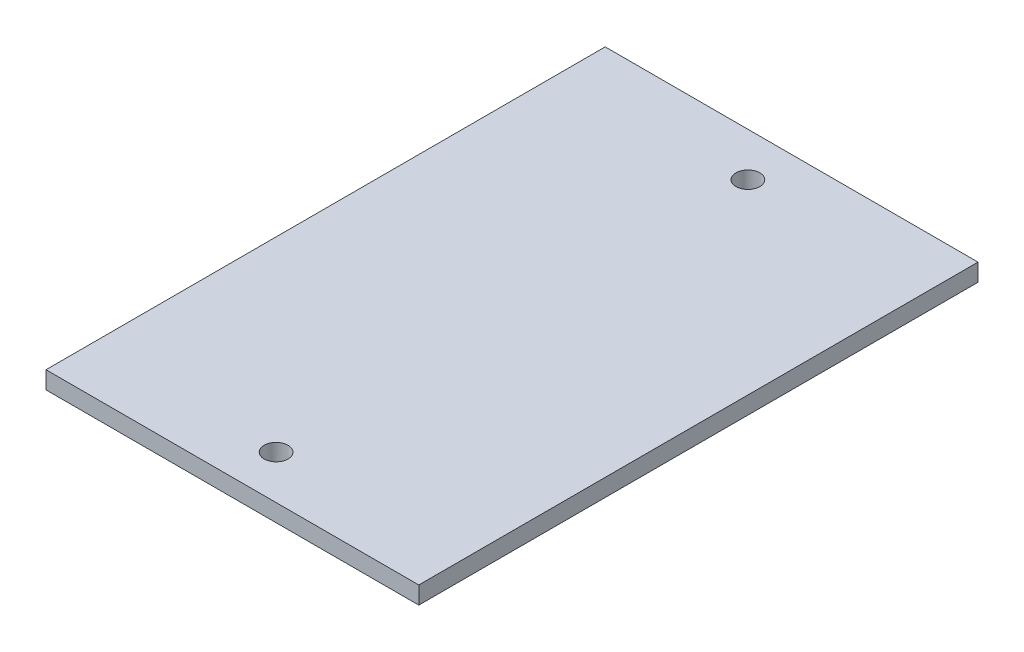
SolidWorks part; units mm, degrees
material "ABS"
ref_plane "Front Plane" through (0, 0, 0) normal (0, 0, 1) x (1, 0, 0)
ref_plane "Top Plane" through (0, 0, 0) normal (0, 1, 0) x (1, 0, 0)
ref_plane "Right Plane" through (0, 0, 0) normal (1, 0, 0) x (0, 0, -1)
sketch "Sketch1" plane through (0, 0, 0) normal (0, 1, 0) x (1, 0, 0)
  line L1 (0, 0) -> (64, 0)
  line L2 (0, 0) -> (0, -96)
  line L3 (0, -96) -> (64, -96)
  line L4 (64, 0) -> (64, -96)
  circle A0 centre (32, -7.5) radius 2.05
  circle A1 centre (32, -88.5) radius 2.05
  point P9 (32, 0)
  point P10 (32, -96)
  dimension "D3" = 4.1
  dimension "D4" = 4.1
  dimension "D1" = 64
  dimension "D2" = 96
  dimension "D5" = 7.5
  dimension "D6" = 7.5
extrude "Boss-Extrude1" add sketch "Sketch1" along normal blind 3
equation "\"Depth\"= 90mm"
equation "\"Height\"= 140mm"
equation "\"Width\"= 64mm"
equation "\"D1@Sketch1\"=\"Width\""
equation "\"D2@Sketch1\"=\"Depth\" +6"
